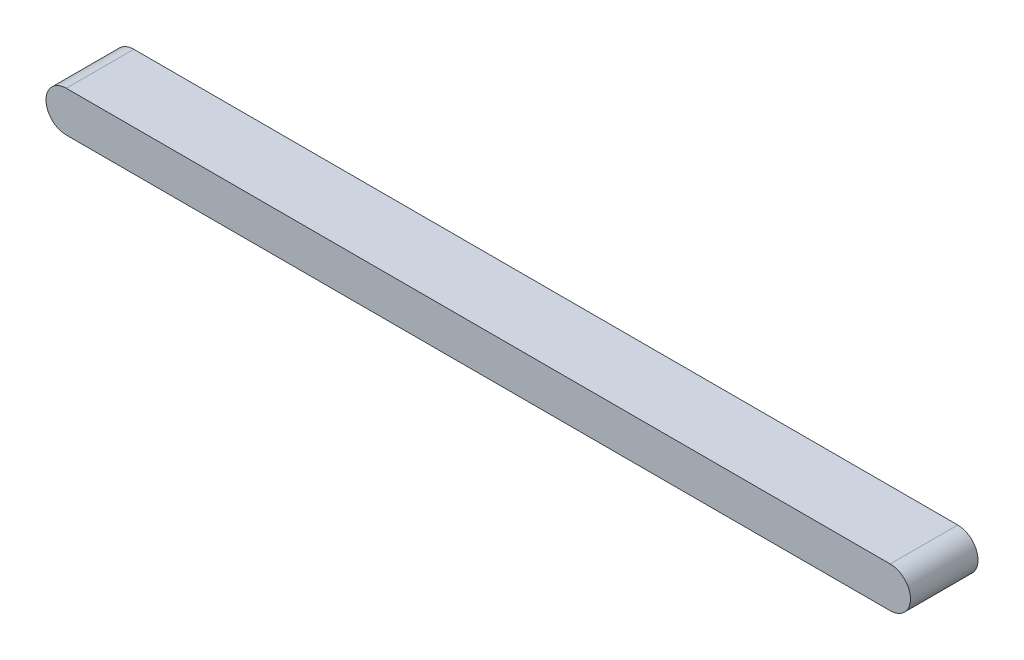
SolidWorks part; units mm, degrees
ref_plane "Front Plane" through (0, 0, 0) normal (0, 0, 1) x (1, 0, 0)
ref_plane "Top Plane" through (0, 0, 0) normal (0, 1, 0) x (1, 0, 0)
ref_plane "Right Plane" through (0, 0, 0) normal (1, 0, 0) x (0, 0, -1)
sketch "Sketch1" plane through (0, 0, 0) normal (0, 0, 1) x (1, 0, 0)
  line L0 (0, 0) -> (122, 0)
  line L2 (0, -6) -> (122, -6)
  arc A0 (0, 0) -> (0, -6) centre (0, -3) ccw
  arc A1 (122, -6) -> (122, 0) centre (122, -3) ccw
  dimension "D1" = 6
  dimension "D2" = 122
extrude "Boss-Extrude1" add sketch "Sketch1" along normal blind 10
